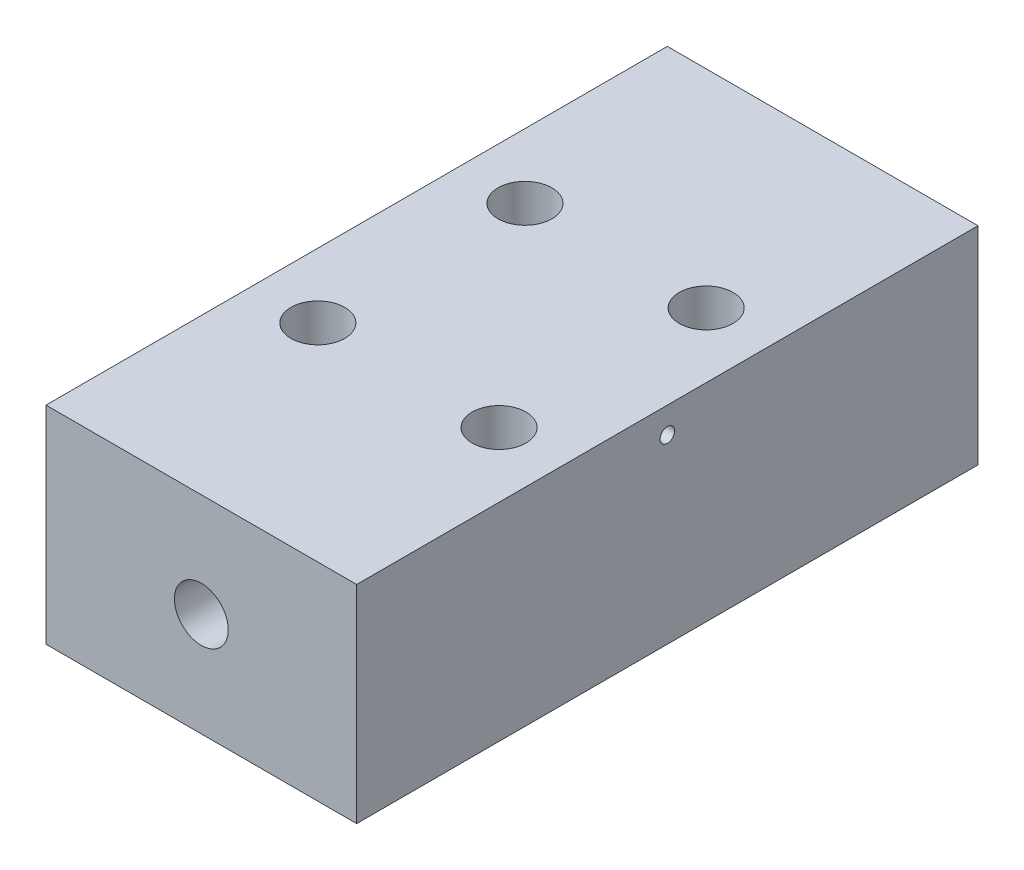
SolidWorks part; units mm, degrees
ref_plane "Front Plane" through (0, 0, 0) normal (0, 0, 1) x (1, 0, 0)
ref_plane "Top Plane" through (0, 0, 0) normal (0, 1, 0) x (1, 0, 0)
ref_plane "Right Plane" through (0, 0, 0) normal (1, 0, 0) x (0, 0, -1)
sketch "Sketch1" plane through (0, 0, 0) normal (0, 0, 1) x (1, 0, 0)
  line L1 (-19.05, 12.7) -> (19.05, 12.7)
  line L2 (-19.05, 12.7) -> (-19.05, -12.7)
  line L3 (-19.05, -12.7) -> (19.05, -12.7)
  line L4 (19.05, 12.7) -> (19.05, -12.7)
  dimension "D1" = 25.4
  dimension "D2" = 38.1
  dimension "D3" = 12.7
  dimension "D4" = 19.05
extrude "Boss-Extrude1" add sketch "Sketch1" along normal blind 76.2
sketch "Sketch2" plane through (0, 0, 76.2) normal (0, 0, 1) x (1, 0, 0)
  circle A0 centre (0, 0) radius 3.302
  dimension "D1" = 6.604
extrude "Cut-Extrude1" cut sketch "Sketch2" against normal through all
sketch "Sketch3" plane through (0, 12.7, 0) normal (0, 1, 0) x (1, 0, 0)
  line L0 (-19.05, -76.2) -> (-19.05, 0) construction
  line L1 (19.05, -76.2) -> (19.05, 0) construction
  line L2 (19.05, 0) -> (-19.05, 0) construction
  circle A0 centre (-11.1125, -25.4) radius 3.302
  circle A1 centre (11.1125, -25.4) radius 3.302
  circle A2 centre (-11.1125, -50.8) radius 3.302
  circle A3 centre (11.1125, -50.8) radius 3.302
  dimension "D1" = 6.604
  dimension "D2" = 7.9375
  dimension "D3" = 7.9375
  dimension "D4" = 25.4
  dimension "D5" = 25.4
extrude "Cut-Extrude2" cut sketch "Sketch3" against normal through all
sketch "Sketch5" plane through (19.05, 0, 0) normal (1, 0, 0) x (0, 0, -1)
  line L0 (-76.2, -12.7) -> (-76.2, 12.7) construction
  line L1 (-76.2, 12.7) -> (0, 12.7) construction
  circle A0 centre (-38.1, 9.525) radius 0.889
  point P4 (-38.1, 12.7)
  dimension "D1" = 1.778
  dimension "D2" = 38.1
  dimension "D3" = 3.175
extrude "Cut-Extrude3" cut sketch "Sketch5" against normal blind 12.7
sketch "Sketch6" plane through (-19.05, 0, 0) normal (-1, 0, 0) x (0, 0, 1)
  circle A0 centre (38.1, 9.525) radius 0.889
  circle A1 centre (38.1, 9.525) radius 0.889 construction
extrude "Cut-Extrude4" cut sketch "Sketch6" against normal blind 12.7
